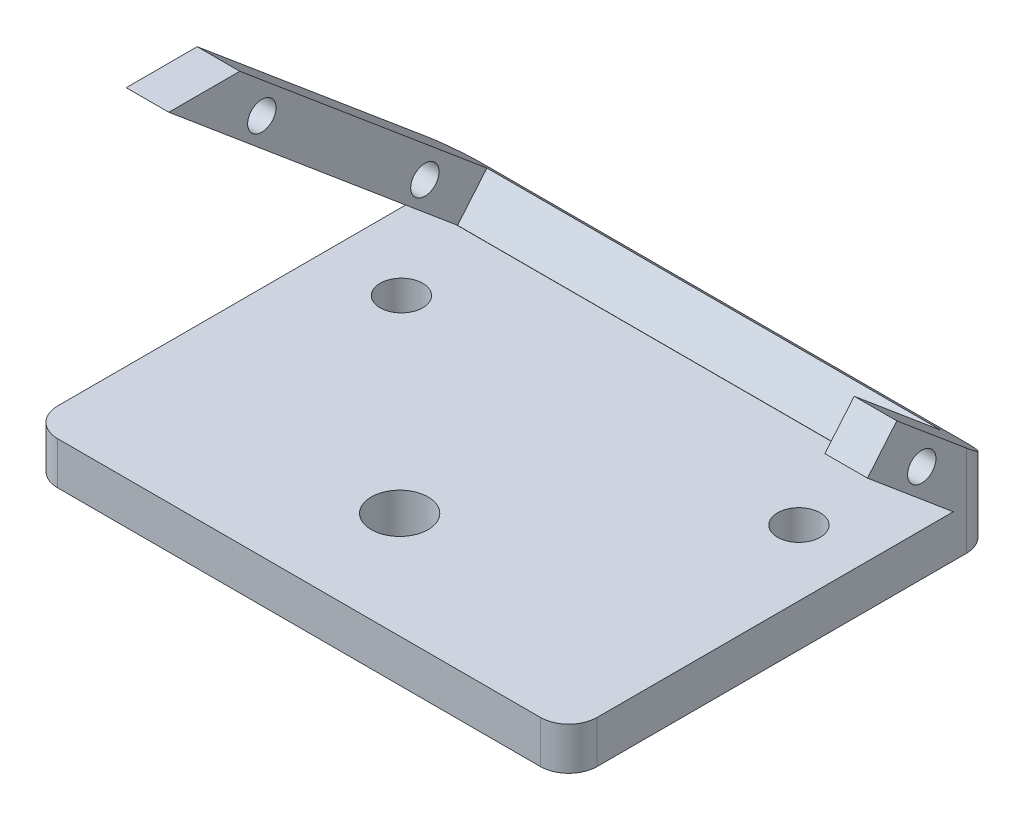
SolidWorks part; units mm, degrees
ref_plane "前视基准面" through (0, 0, 0) normal (0, 0, 1) x (1, 0, 0)
ref_plane "上视基准面" through (0, 0, 0) normal (0, 1, 0) x (1, 0, 0)
ref_plane "右视基准面" through (0, 0, 0) normal (1, 0, 0) x (0, 0, -1)
other "Configuration Table"
sketch "草图1" plane through (0, 0, 0) normal (0, 1, 0) x (1, 0, 0)
  line L1 (-27.4408, 6.0208) -> (10.5592, 6.0208)
  line L2 (-27.4408, 6.0208) -> (-27.4408, -23.9792)
  line L3 (-27.4408, -23.9792) -> (10.5592, -23.9792)
  line L4 (10.5592, 6.0208) -> (10.5592, -23.9792)
  dimension "D1" = 38
  dimension "D2" = 30
extrude "凸台-拉伸1" add sketch "草图1" along normal blind 20
sketch "草图2" plane through (-27.4408, 0, 0) normal (-1, 0, 0) x (0, 0, 1)
  line L0 (23.9792, 3) -> (-3.1081, 3)
  line L1 (23.9792, 20) -> (23.9792, 0) construction
  line L2 (-3.1081, 3) -> (17.1517, 20)
  line L3 (17.1517, 20) -> (12.1517, 20)
  line L4 (-6.0208, 20) -> (23.9792, 20) construction
  line L5 (12.1517, 20) -> (-6.0208, 4.7515)
  line L6 (-6.0208, 20) -> (-6.0208, 0) construction
  line L7 (-6.0208, 4.7515) -> (-6.0208, 0)
  line L8 (-6.0208, 0) -> (23.9792, 0) construction
  line L9 (-6.0208, 0) -> (23.9792, 0)
  line L10 (23.9792, 0) -> (23.9792, 3)
  dimension "D1" = 3
  dimension "D2" = 5
  dimension "D3" = 40
extrude "切除-拉伸1" cut sketch "草图2" against normal through all flip side to cut
sketch "草图4" plane through (0, 5.753, -4.8273) normal (0, 0.766, -0.6428) x (1, 0, 0)
  line L0 (-24.4408, -25.9947) -> (-24.4408, 0.558)
  line L1 (10.5592, 1.558) -> (-27.4408, 1.558) construction
  line L3 (-24.4408, 0.558) -> (7.5592, 0.558)
  line L4 (7.5592, 0.558) -> (7.5592, -7.442)
  line L5 (7.5592, -7.442) -> (10.5592, -7.442)
  line L6 (10.5592, -22.1645) -> (10.5592, 1.558) construction
  line L7 (10.5592, -7.442) -> (10.5592, -25.9947)
  line L8 (10.5592, -25.9947) -> (-24.4408, -25.9947)
  line L11 (-27.4408, -22.1645) -> (-27.4408, 1.558) construction
  point P11 (10.5592, -25.9947)
  dimension "D1" = 3
  dimension "D2" = 3
  dimension "D3" = 8
  dimension "D4" = 1
extrude "切除-拉伸2" cut sketch "草图4" against normal up to surface (3.2139 mm away) up to face at (-8.4408, 11.5, 7.0218)
sketch "草图5" plane through (-27.4408, 0, 0) normal (-1, 0, 0) x (0, 0, 1)
  circle A0 centre (-0.8864, 6.864) radius 1
  circle A1 centre (10.5992, 16.5119) radius 1
  point P4 (0, 0)
  dimension "D1" = 2
  dimension "D2" = 2
  dimension "D3" = 15
extrude "切除-拉伸3" cut sketch "草图5" against normal through all
sketch "草图6" plane through (0, 3, 0) normal (0, 1, 0) x (1, 0, 0)
  circle A0 centre (-8.8451, -16.4858) radius 2
  point P2 (-8.8451, -16.4858)
  point P3 (0, 0)
  dimension "D1" = 4
sketch "草图7" plane through (0, 3, 0) normal (0, 1, 0) x (1, 0, 0)
  circle A0 centre (-22.0691, -3.1397) radius 1.5
  circle A1 centre (5.9309, -3.1397) radius 1.5
  point P4 (5.9309, -3.1397)
  dimension "D1" = 3
  dimension "D2" = 3
  dimension "D3" = 28
extrude "切除-拉伸4" cut sketch "草图6" against normal through all
extrude "切除-拉伸5" cut sketch "草图7" against normal through all
fillet "圆角1" radius 2 4 edges at (10.5592, 2.3757, -6.0208) (-27.4408, 2.3757, -6.0208) (10.5592, 1.5, 23.9792) (-27.4408, 1.5, 23.9792)
